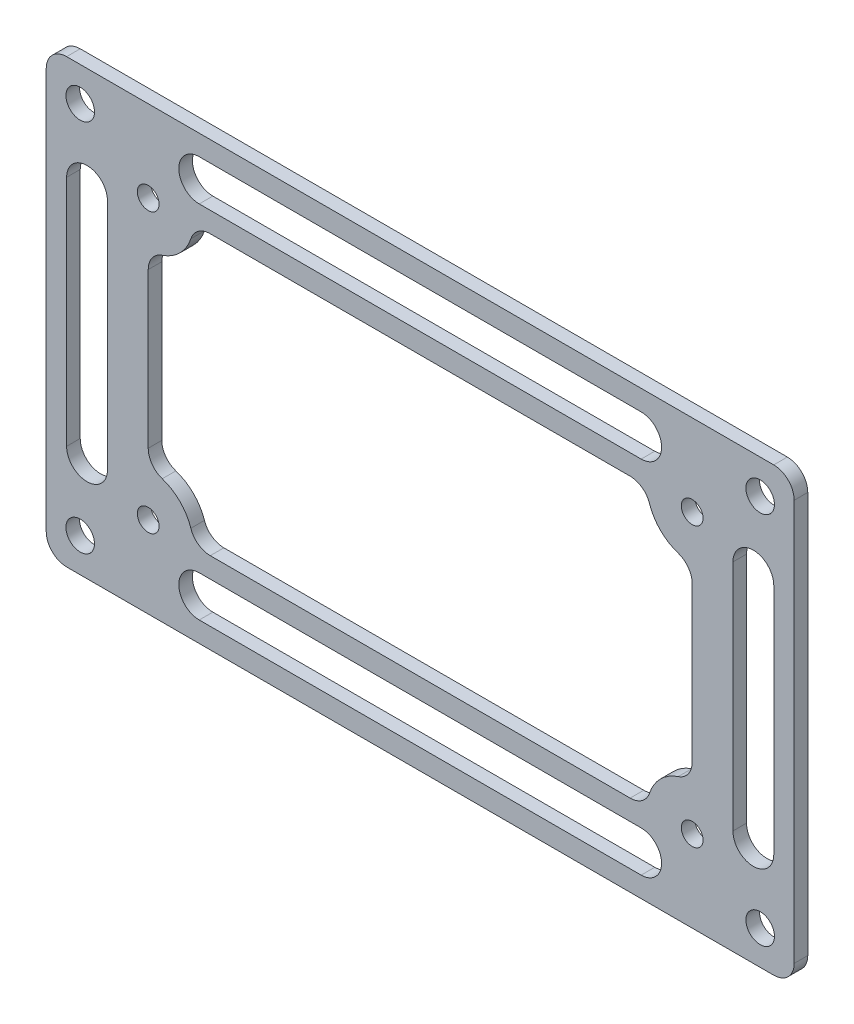
SolidWorks part; units mm, degrees
material "5052-H34"
ref_plane "正面" through (0, 0, 0) normal (0, 0, 1) x (1, 0, 0)
ref_plane "平面" through (0, 0, 0) normal (0, 1, 0) x (1, 0, 0)
ref_plane "右側面" through (0, 0, 0) normal (1, 0, 0) x (0, 0, -1)
sketch "ｽｹｯﾁ1" plane through (0, 0, 0) normal (0, 0, 1) x (1, 0, 0)
  line L0 (0, 20.5) -> (0, 0) construction
  line L1 (-40, 20.5) -> (40, 20.5) construction
  line L2 (-40, 20.5) -> (-40, -20.5) construction
  line L3 (-40, -20.5) -> (40, -20.5) construction
  line L4 (40, 20.5) -> (40, -20.5) construction
  line L5 (-40, 20.5) -> (40, -20.5) construction
  line L6 (-40, -20.5) -> (40, 20.5) construction
  line L7 (0, 0) -> (40, 0) construction
  line L9 (-55, 32.5) -> (55, 32.5)
  line L10 (-55, 32.5) -> (-55, -32.5)
  line L11 (-55, -32.5) -> (55, -32.5)
  line L12 (55, 32.5) -> (55, -32.5)
  line L13 (-55, 32.5) -> (55, -32.5) construction
  line L14 (-55, -32.5) -> (55, 32.5) construction
  line L15 (-50, 27.5) -> (50, 27.5) construction
  line L16 (-50, 27.5) -> (-50, -27.5) construction
  line L17 (-50, -27.5) -> (50, -27.5) construction
  line L18 (50, 27.5) -> (50, -27.5) construction
  line L19 (-50, 27.5) -> (50, -27.5) construction
  line L20 (-50, -27.5) -> (50, 27.5) construction
  circle A0 centre (40, 20.5) radius 1.6
  circle A1 centre (-40, 20.5) radius 1.6
  circle A2 centre (-40, -20.5) radius 1.6
  circle A3 centre (40, -20.5) radius 1.6
  circle A4 centre (50, 27.5) radius 2.1
  circle A5 centre (50, -27.5) radius 2.1
  circle A6 centre (-50, 27.5) radius 2.1
  circle A7 centre (-50, -27.5) radius 2.1
  point P0 (0, 0)
  dimension "D3" = 3.2
  dimension "D8" = 4.2
  dimension "D1" = 80
  dimension "D2" = 41
  dimension "D4" = 110
  dimension "D5" = 65
  dimension "D6" = 100
  dimension "D7" = 55
extrude "ﾎﾞｽ - 押し出し1" add sketch "ｽｹｯﾁ1" along normal blind 2
sketch "ｽｹｯﾁ3" plane through (0, 0, 2) normal (0, 0, 1) x (1, 0, 0)
  line L0 (-38.4, 20.5) -> (-33.4, 20.5) construction
  line L1 (-40, -20.5) -> (-38.4, -20.5) construction
  line L2 (-40, -13.9) -> (-40, 13.9)
  line L3 (-40, 20.5) -> (-38.4, 20.5) construction
  line L4 (40, -13.9) -> (40, 13.9)
  line L5 (-40, -20.5) -> (40, 20.5) construction
  line L6 (-40, 20.5) -> (40, -20.5) construction
  line L7 (-33.4, 20.5) -> (33.4, 20.5)
  line L8 (-40, 13.9) -> (-40, 18.9) construction
  line L9 (-40, 18.9) -> (-40, 20.5) construction
  line L10 (-38.4, -20.5) -> (-33.4, -20.5) construction
  line L11 (-33.4, -20.5) -> (33.4, -20.5)
  line L12 (-40, -20.5) -> (-40, -18.9) construction
  line L13 (-40, -18.9) -> (-40, -13.9) construction
  line L14 (38.4, -20.5) -> (40, -20.5) construction
  line L15 (40, -20.5) -> (40, -18.9) construction
  line L16 (33.4, -20.5) -> (38.4, -20.5) construction
  line L17 (40, -18.9) -> (40, -13.9) construction
  line L18 (33.4, 20.5) -> (38.4, 20.5) construction
  line L19 (38.4, 20.5) -> (40, 20.5) construction
  line L20 (40, 13.9) -> (40, 18.9) construction
  line L21 (40, 18.9) -> (40, 20.5) construction
  line L22 (0, 0) -> (0, 32.5) construction
  line L23 (55, 32.5) -> (-55, 32.5) construction
  line L24 (0, 0) -> (55, 0) construction
  line L25 (55, -32.5) -> (55, 32.5) construction
  line L26 (-32.4956, 26.495) -> (32.4956, 26.495) construction
  line L27 (-32.4956, 29.5) -> (32.4956, 29.5)
  line L28 (-32.4956, 23.49) -> (32.4956, 23.49)
  line L29 (-32.4956, -26.495) -> (32.4956, -26.495) construction
  line L30 (-32.4956, -29.5) -> (32.4956, -29.5)
  line L31 (-32.4956, -23.49) -> (32.4956, -23.49)
  line L32 (48.995, 17.1316) -> (48.995, -17.1316) construction
  line L33 (52, 17.1316) -> (52, -17.1316)
  line L34 (45.99, 17.1316) -> (45.99, -17.1316)
  line L35 (-48.995, 17.1316) -> (-48.995, -17.1316) construction
  line L36 (-52, 17.1316) -> (-52, -17.1316)
  line L37 (-45.99, 17.1316) -> (-45.99, -17.1316)
  arc A0 (-40, 13.9) -> (-33.4, 20.5) centre (-40, 20.5) ccw
  circle A1 centre (-50, -27.5) radius 2.1
  circle A2 centre (-50, -27.5) radius 2.1 construction
  circle A3 centre (-50, 27.5) radius 2.1
  circle A4 centre (-50, 27.5) radius 2.1 construction
  circle A5 centre (-40, 20.5) radius 1.6
  arc A6 (-40, 18.9) -> (-38.5761, 19.7703) centre (-40, 20.5) ccw construction
  circle A7 centre (40, -20.5) radius 1.6
  arc A8 (38.5761, -19.7703) -> (38.4, -20.5) centre (40, -20.5) ccw construction
  circle A9 centre (50, -27.5) radius 2.1
  circle A10 centre (50, -27.5) radius 2.1 construction
  circle A11 centre (40, 20.5) radius 1.6
  arc A12 (38.4, 20.5) -> (38.5761, 19.7703) centre (40, 20.5) ccw construction
  circle A13 centre (-40, -20.5) radius 1.6
  arc A14 (-38.4, -20.5) -> (-38.5761, -19.7703) centre (-40, -20.5) ccw construction
  circle A15 centre (50, 27.5) radius 2.1
  circle A16 centre (50, 27.5) radius 2.1 construction
  arc A17 (-33.4, -20.5) -> (-40, -13.9) centre (-40, -20.5) ccw
  arc A18 (40, -13.9) -> (33.4, -20.5) centre (40, -20.5) ccw
  arc A19 (33.4, 20.5) -> (40, 13.9) centre (40, 20.5) ccw
  arc A20 (-33.4, 20.5) -> (-40, 13.9) centre (-40, 20.5) ccw construction
  circle A21 centre (-40, 20.5) radius 6.6 construction
  arc A22 (-38.4, 20.5) -> (-40, 18.9) centre (-40, 20.5) ccw construction
  circle A23 centre (-40, 20.5) radius 1.6 construction
  arc A24 (-38.5761, 19.7703) -> (-38.4, 20.5) centre (-40, 20.5) ccw construction
  arc A25 (-40, -13.9) -> (-33.4, -20.5) centre (-40, -20.5) ccw construction
  circle A26 centre (-40, -20.5) radius 6.6 construction
  arc A27 (-40, -18.9) -> (-38.4, -20.5) centre (-40, -20.5) ccw construction
  circle A28 centre (-40, -20.5) radius 1.6 construction
  arc A29 (-38.5761, -19.7703) -> (-40, -18.9) centre (-40, -20.5) ccw construction
  arc A30 (33.4, -20.5) -> (40, -13.9) centre (40, -20.5) ccw construction
  circle A31 centre (40, -20.5) radius 6.6 construction
  arc A32 (38.4, -20.5) -> (40, -18.9) centre (40, -20.5) ccw construction
  circle A33 centre (40, -20.5) radius 1.6 construction
  arc A34 (40, -18.9) -> (38.5761, -19.7703) centre (40, -20.5) ccw construction
  arc A35 (40, 13.9) -> (33.4, 20.5) centre (40, 20.5) ccw construction
  circle A36 centre (40, 20.5) radius 6.6 construction
  arc A37 (40, 18.9) -> (38.4, 20.5) centre (40, 20.5) ccw construction
  circle A38 centre (40, 20.5) radius 1.6 construction
  arc A39 (38.5761, 19.7703) -> (40, 18.9) centre (40, 20.5) ccw construction
  arc A40 (-32.4956, 29.5) -> (-32.4956, 23.49) centre (-32.4956, 26.495) ccw
  arc A41 (32.4956, 23.49) -> (32.4956, 29.5) centre (32.4956, 26.495) ccw
  arc A42 (-32.4956, -29.5) -> (-32.4956, -23.49) centre (-32.4956, -26.495) cw
  arc A43 (32.4956, -23.49) -> (32.4956, -29.5) centre (32.4956, -26.495) cw
  arc A44 (52, 17.1316) -> (45.99, 17.1316) centre (48.995, 17.1316) ccw
  arc A45 (45.99, -17.1316) -> (52, -17.1316) centre (48.995, -17.1316) ccw
  arc A46 (-52, 17.1316) -> (-45.99, 17.1316) centre (-48.995, 17.1316) cw
  arc A47 (-45.99, -17.1316) -> (-52, -17.1316) centre (-48.995, -17.1316) cw
  point P32 (0, 0)
  point P63 (0, 26.495)
  point P70 (0, -26.495)
  point P77 (48.995, 0)
  point P84 (-48.995, 0)
  dimension "D10" = 3.005
  dimension "D13" = 3.005
  dimension "D11" = 3
  dimension "D14" = 3
  dimension "D1" = 0
  dimension "D2" = 0
  dimension "D3" = 0
  dimension "D4" = 0
  dimension "D5" = 0
  dimension "D6" = 0
  dimension "D7" = 0
  dimension "D8" = 0
  dimension "D9" = 5
extrude "ｶｯﾄ - 押し出し1" cut sketch "ｽｹｯﾁ3" against normal through all
fillet "ﾌｨﾚｯﾄ1" radius 3.005 12 edges at (-55, -32.5, 1) (55, -32.5, 1) (55, 32.5, 1) (-55, 32.5, 1) (-33.4, 20.5, 1) (-40, 13.9, 1) (33.4, 20.5, 1) (40, 13.9, 1) (40, -13.9, 1) (33.4, -20.5, 1) (-33.4, -20.5, 1) (-40, -13.9, 1)
